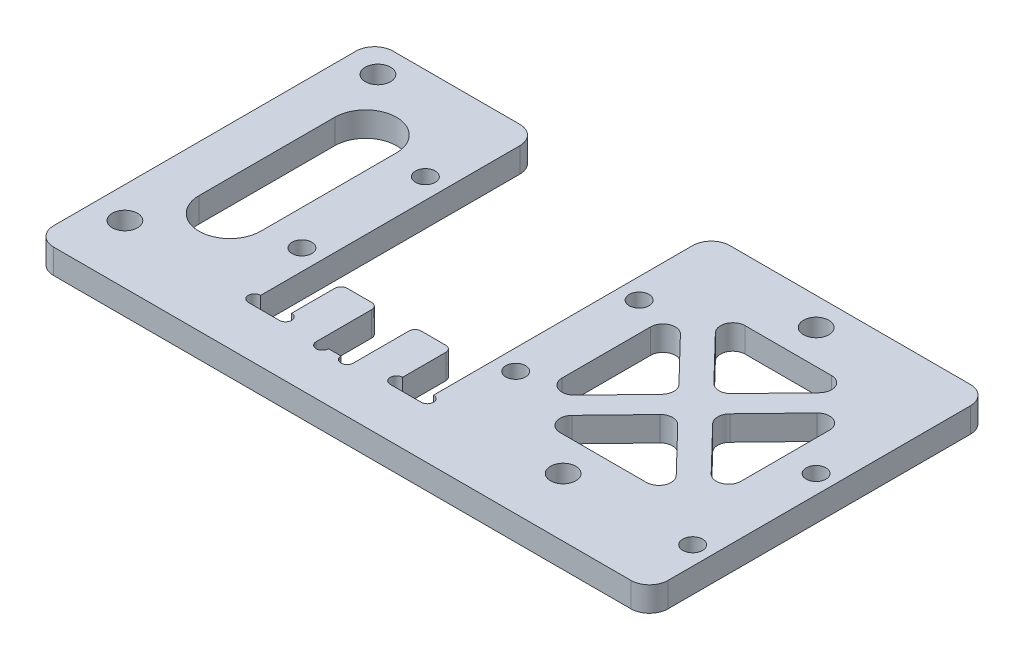
SolidWorks part; units mm, degrees
material "Thornel Mat VMA"
ref_plane "前视基准面" through (0, 0, 0) normal (0, 0, 1) x (1, 0, 0)
ref_plane "上视基准面" through (0, 0, 0) normal (0, 1, 0) x (1, 0, 0)
ref_plane "右视基准面" through (0, 0, 0) normal (1, 0, 0) x (0, 0, -1)
other "Configuration Table"
sketch "草图1" plane through (0, 0, 0) normal (0, 1, 0) x (1, 0, 0)
  line L1 (-27.5, 30) -> (27.5, 30)
  line L2 (-27.5, 30) -> (-27.5, -30)
  line L3 (-27.5, -30) -> (27.5, -30)
  line L4 (27.5, 30) -> (27.5, -30)
  line L5 (-27.5, 30) -> (27.5, -30) construction
  line L6 (-27.5, -30) -> (27.5, 30) construction
  line L7 (-14.01, 22) -> (14.01, 22)
  line L8 (-14.01, 22) -> (-14.01, -22)
  line L9 (-14.01, -22) -> (14.01, -22)
  line L10 (14.01, 22) -> (14.01, -22)
  line L11 (-14.01, 22) -> (14.01, -22) construction
  line L12 (-14.01, -22) -> (14.01, 22) construction
  line L13 (-14.01, 22) -> (14.01, 22)
  line L14 (-14.01, 22) -> (-14.01, 30)
  line L15 (-14.01, 30) -> (14.01, 30)
  line L16 (14.01, 22) -> (14.01, 30)
  point P0 (0, 0)
  point P6 (0, 0)
  dimension "D1" = 55
  dimension "D2" = 28.02
  dimension "D3" = 44
  dimension "D4" = 60
extrude "凸台-拉伸1" add sketch "草图1" along normal blind 4 contours L16 L10 L9 L8 L14 L1 L2 L3 L4
sketch "草图2" plane through (0, 4, 0) normal (0, 1, 0) x (1, 0, 0)
  line L0 (-14.01, -22) -> (14.01, -22) construction
  line L1 (-8.99, -22) -> (-3.01, -22)
  line L2 (-8.99, -22) -> (-8.99, -12)
  line L3 (-8.99, -12) -> (-3.01, -12)
  line L4 (-3.01, -22) -> (-3.01, -12)
  line L5 (-9, -46.1224) -> (-9, 2.4742) construction
  line L6 (3.01, -22) -> (8.99, -22)
  line L7 (3.01, -22) -> (3.01, -12)
  line L8 (3.01, -12) -> (8.99, -12)
  line L9 (8.99, -22) -> (8.99, -12)
  line L10 (-3, -16.6222) -> (-3, -12.3531) construction
  line L11 (3, -48.1112) -> (3, -44.2368) construction
  dimension "D1" = 0.01
  dimension "D2" = 0.01
  dimension "D3" = 0.01
  dimension "D4" = 10
extrude "凸台-拉伸2" add sketch "草图2" against normal blind 4
sketch "草图4" plane through (0, 0, 0) normal (0, -1, 0) x (1, 0, 0)
  line L0 (27.5, -30) -> (27.5, 30) construction
  line L1 (-27.5, -30) -> (27.5, -30)
  line L2 (-27.5, -30) -> (-27.5, -22)
  line L3 (-27.5, -22) -> (27.5, -22)
  line L4 (27.5, -30) -> (27.5, -22)
  line L5 (8.99, 22) -> (8.99, 12) construction
  line L6 (14.01, 22) -> (14.01, -30) construction
  line L7 (-3.01, 22) -> (3.01, 22) construction
  line L8 (-14.01, -30) -> (-14.01, 22) construction
  line L9 (-8.99, 12) -> (-8.99, 22) construction
  circle A0 centre (8.99, 21) radius 1
  circle A1 centre (14.01, 21) radius 1
  circle A2 centre (-2.01, 22) radius 1
  circle A3 centre (2.01, 22) radius 1
  circle A4 centre (-14.01, 21) radius 1
  circle A5 centre (-8.99, 21) radius 1
  dimension "D2" = 2
  dimension "D1" = 8
extrude "切除-拉伸1" cut sketch "草图4" against normal blind 4
sketch "草图5" plane through (0, 0, 0) normal (0, -1, 0) x (1, 0, 0)
  line L0 (14.01, 20) -> (14.01, -22) construction
  line L1 (-17.01, 10) -> (17.01, 10) construction
  line L2 (-17.01, 10) -> (-17.01, -10) construction
  line L3 (-17.01, -10) -> (17.01, -10) construction
  line L4 (17.01, 10) -> (17.01, -10) construction
  line L5 (-17.01, 10) -> (17.01, -10) construction
  line L6 (-17.01, -10) -> (17.01, 10) construction
  line L7 (-14.01, -22) -> (-14.01, 20) construction
  line L9 (27.5, -22) -> (27.5, 30) construction
  line L10 (-27.5, 30) -> (27.5, 30) construction
  line L11 (0, -25.6277) -> (0, 34.1238) construction
  line L12 (8.99, 22) -> (14.01, 22) construction
  circle A0 centre (17.01, 10) radius 1.6
  circle A1 centre (17.01, -10) radius 1.6
  circle A2 centre (-17.01, -10) radius 1.6
  circle A3 centre (-17.01, 10) radius 1.6
  circle A4 centre (24.5, 25) radius 1.6 construction
  circle A5 centre (24.5, 5) radius 1.6 construction
  circle A6 centre (-24.5, 5) radius 1.6 construction
  circle A7 centre (-24.5, 25) radius 1.6 construction
  point P0 (0, 0)
  dimension "D5" = 3.2
  dimension "D1" = 20
  dimension "D2" = 3
  dimension "D3" = 3
  dimension "D4" = 22
  dimension "D6" = 20
  dimension "D7" = 3
  dimension "D8" = 5
extrude "切除-拉伸2" cut sketch "草图5" against normal blind 4
sketch "草图6" plane through (0, 0, 0) normal (0, -1, 0) x (1, 0, 0)
  line L0 (27.5, -22) -> (14.01, -22) construction
  line L1 (27.5, 30) -> (59, 30)
  line L2 (27.5, 30) -> (27.5, -22)
  line L3 (27.5, -22) -> (59, -22)
  line L4 (59, 30) -> (59, -22)
  dimension "D1" = 31.5
extrude "凸台-拉伸3" add sketch "草图6" against normal blind 4
sketch "草图7" plane through (0, 0, 0) normal (0, -1, 0) x (1, 0, 0)
  line L0 (59, -22) -> (59, 30) construction
  line L4 (56, 20) -> (56, 0) construction
  line L5 (-27.5, 30) -> (59, 30) construction
  circle A0 centre (56, 20) radius 1.6
  circle A1 centre (56, 0) radius 1.6
  dimension "D4" = 3.2
  dimension "D1" = 3
  dimension "D2" = 10
  dimension "D3" = 20
extrude "切除-拉伸3" cut sketch "草图7" against normal blind 4
sketch "草图8" plane through (0, 0, 0) normal (0, -1, 0) x (1, 0, 0)
  line L0 (14.01, 20) -> (14.01, -22) construction
  line L1 (59, -22) -> (14.01, -22)
  line L2 (59, -22) -> (59, -25)
  line L3 (59, -25) -> (14.01, -25)
  line L4 (14.01, -22) -> (14.01, -25)
  line L5 (-14.01, -22) -> (-40.557, -22)
  line L6 (-14.01, -22) -> (-14.01, -25)
  line L7 (-14.01, -25) -> (-40.557, -25)
  line L8 (-40.557, -22) -> (-40.557, -25)
  line L9 (-27.5, 30) -> (-40.557, 30)
  line L10 (-27.5, 30) -> (-27.5, -22)
  line L11 (-27.5, -22) -> (-40.557, -22)
  line L12 (-40.557, 30) -> (-40.557, -22)
  circle A0 centre (35.507, 20.5) radius 2.05 construction
  circle A1 centre (35.507, -20.5) radius 2.05 construction
  circle A2 centre (-35.507, -20.5) radius 2.05 construction
  circle A3 centre (-35.507, 20.5) radius 2.05 construction
  line M11 (-27.5, 30) -> (-27.5, -22)
  line M12 (-27.5, -22) -> (-14.01, -22)
  line M30 (14.01, -22) -> (59, -22)
  dimension "D1" = 4.1
  dimension "D2" = 3
  dimension "D3" = 3
extrude "凸台-拉伸4" add sketch "草图8" against normal up to surface (4 mm away) contours L9 L12 L5 M11 | L5 L8 L7 L6 M12 | L4 L3 L2 M30 up to face at (56, 4, -1.6)
sketch "草图10" plane through (0, 0, 0) normal (0, -1, 0) x (1, 0, 0)
  circle A0 centre (-35.507, -20.5) radius 2.05
  circle A1 centre (-35.507, 20.5) radius 2.05
  circle A2 centre (35.507, 20.5) radius 2.05
  circle A3 centre (35.507, -20.5) radius 2.05
  dimension "D1" = 4.1
extrude "切除-拉伸4" cut sketch "草图10" against normal blind 10
fillet "圆角1" radius 1 4 edges at (8.99, 2, 12) (3.01, 2, 12) (-3.01, 2, 12) (-8.99, 2, 12)
fillet "圆角2" radius 3 6 edges at (59, 2, -25) (59, 2, 30) (-40.557, 2, 30) (-40.557, 2, -25) (14.01, 2, -25) (-14.01, 2, -25)
sketch "草图11" plane through (0, 4, 0) normal (0, 1, 0) x (1, 0, 0)
  line L0 (-28, 11) -> (-28, -11) construction
  line L1 (22.01, 15) -> (51, 15)
  line L2 (22.01, 15) -> (22.01, -15)
  line L3 (22.01, -15) -> (51, -15)
  line L4 (51, 15) -> (51, -15)
  line L5 (-23, 11) -> (-23, -11)
  line L6 (-33, 11) -> (-33, -11)
  arc A0 (-23, 11) -> (-33, 11) centre (-28, 11) ccw
  arc A1 (-33, -11) -> (-23, -11) centre (-28, -11) ccw
  circle A2 centre (17.01, -10) radius 1.6 construction
  circle A3 centre (56, 0) radius 1.6 construction
  circle A4 centre (35.507, 20.5) radius 2.05 construction
  circle A5 centre (35.507, -20.5) radius 2.05 construction
  point P6 (-28, 0)
  dimension "D3" = 5
  dimension "D1" = 28
  dimension "D2" = 22
  dimension "D4" = 5
  dimension "D5" = 5
  dimension "D6" = 5.5
  dimension "D7" = 5.5
extrude "切除-拉伸5" cut sketch "草图11" against normal blind 10
sketch "草图12" plane through (0, 4, 0) normal (0, 1, 0) x (1, 0, 0)
  line L0 (22.01, 15) -> (51, -15)
  line L1 (22.01, -15) -> (51, 15)
extrude "拉伸-薄壁1" add sketch "草图12" against normal blind 4 thin thin type mid plane wall 4
fillet "圆角3" radius 2 12 edges at (39.2862, 2, 0) (51, 2, -12.1219) (51, 2, 12.1219) (24.7912, 2, 15) (48.2188, 2, 15) (48.2188, 2, -15) (36.505, 2, -2.8781) (24.7912, 2, -15) (33.7238, 2, 0) (22.01, 2, 12.1219) (22.01, 2, -12.1219) (36.505, 2, 2.8781)
sketch "草图13" plane through (0, 0, 0) normal (0, -1, 0) x (1, 0, 0)
  circle A0 centre (17.01, -10) radius 1.6 construction
  circle A1 centre (17.01, 10) radius 1.6 construction
  circle A2 centre (-17.01, -10) radius 1.6 construction
  circle A3 centre (-17.01, 10) radius 1.6 construction
  circle A4 centre (17.01, -10) radius 1.6
  circle A5 centre (17.01, 10) radius 1.6
  circle A6 centre (-17.01, -10) radius 1.6
  circle A7 centre (-17.01, 10) radius 1.6
extrude "凸台-拉伸5" add sketch "草图13" against normal blind 4
sketch "草图15" plane through (0, 0, 0) normal (0, -1, 0) x (1, 0, 0)
  circle A0 centre (-17.3205, -10) radius 1.6
  circle A1 centre (-17.3205, 10) radius 1.6
  circle A2 centre (17.3205, 10) radius 1.6
  circle A3 centre (17.3205, -10) radius 1.6
  dimension "D1" = 3.2
extrude "切除-拉伸6" cut sketch "草图15" against normal blind 4
